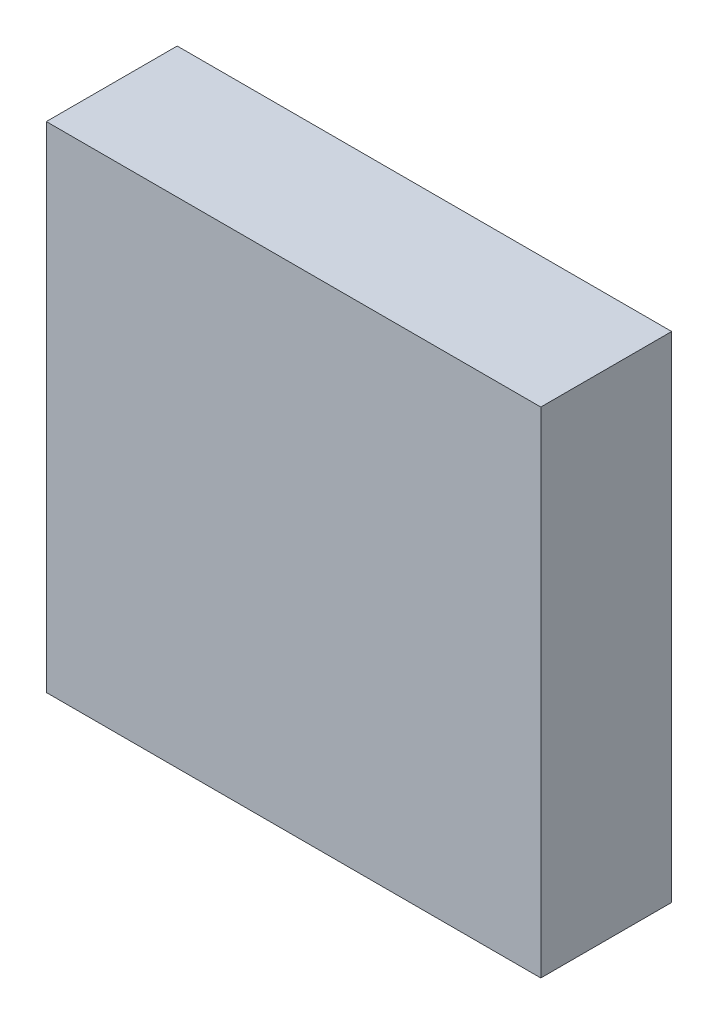
SolidWorks part; units mm, degrees
ref_plane "Front Plane" through (0, 0, 0) normal (0, 0, 1) x (1, 0, 0)
ref_plane "Top Plane" through (0, 0, 0) normal (0, 1, 0) x (1, 0, 0)
ref_plane "Right Plane" through (0, 0, 0) normal (1, 0, 0) x (0, 0, -1)
sketch "Sketch1" plane through (0, 0, 0) normal (0, 0, 1) x (1, 0, 0)
  line L1 (-7.5, -7.5) -> (7.5, -7.5)
  line L2 (-7.5, -7.5) -> (-7.5, 7.5)
  line L3 (-7.5, 7.5) -> (7.5, 7.5)
  line L4 (7.5, -7.5) -> (7.5, 7.5)
  line L5 (-7.5, -7.5) -> (7.5, 7.5) construction
  line L6 (-7.5, 7.5) -> (7.5, -7.5) construction
  point P0 (0, 0)
  dimension "D1" = 15
  dimension "D2" = 15
extrude "Boss-Extrude1" add sketch "Sketch1" along normal blind 3.97
